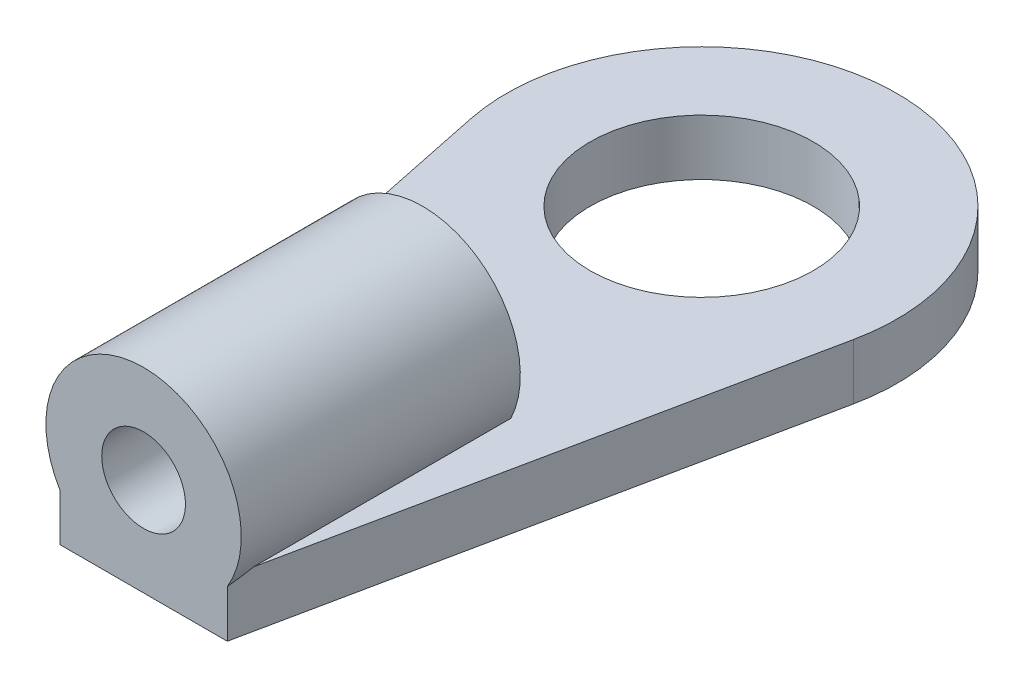
SolidWorks part; units mm, degrees
ref_plane "前视基准面" through (0, 0, 0) normal (0, 0, 1) x (1, 0, 0)
ref_plane "上视基准面" through (0, 0, 0) normal (0, 1, 0) x (1, 0, 0)
ref_plane "右视基准面" through (0, 0, 0) normal (1, 0, 0) x (0, 0, -1)
other "Configuration Table"
sketch "草图1" plane through (0, 0, 0) normal (0, 1, 0) x (1, 0, 0)
  line L0 (0, 0) -> (0, -10) construction
  line L1 (-1.5, -10) -> (1.5, -10)
  line L2 (-1.5, -10) -> (-3.427, -0.7109)
  line L3 (1.5, -10) -> (3.427, -0.7109)
  circle A0 centre (0, 0) radius 2
  arc A1 (3.427, -0.7109) -> (-3.427, -0.7109) centre (0, 0) ccw
  point P8 (0, -10)
  dimension "D1" = 4
  dimension "D2" = 7
  dimension "D3" = 10
  dimension "D4" = 1.5
extrude "凸台-拉伸1" add sketch "草图1" along normal blind 1
sketch "草图2" plane through (0, 0, 0) normal (0, 0, 1) x (1, 0, 0)
  line L0 (0, 0) -> (0, 1.75) construction
  line L1 (1.5, 0) -> (0, 0) construction
  circle A2 centre (0, 1.75) radius 1.75
  dimension "D1" = 1.75
extrude "凸台-拉伸2" add sketch "草图2" against normal blind 5 from offset 10
sketch "草图3" plane through (0, 0, 5) normal (0, 0, -1) x (-1, 0, 0)
  circle A0 centre (0, 1.75) radius 0.75
  dimension "D1" = 1.5
extrude "切除-拉伸1" cut sketch "草图3" against normal blind 5
